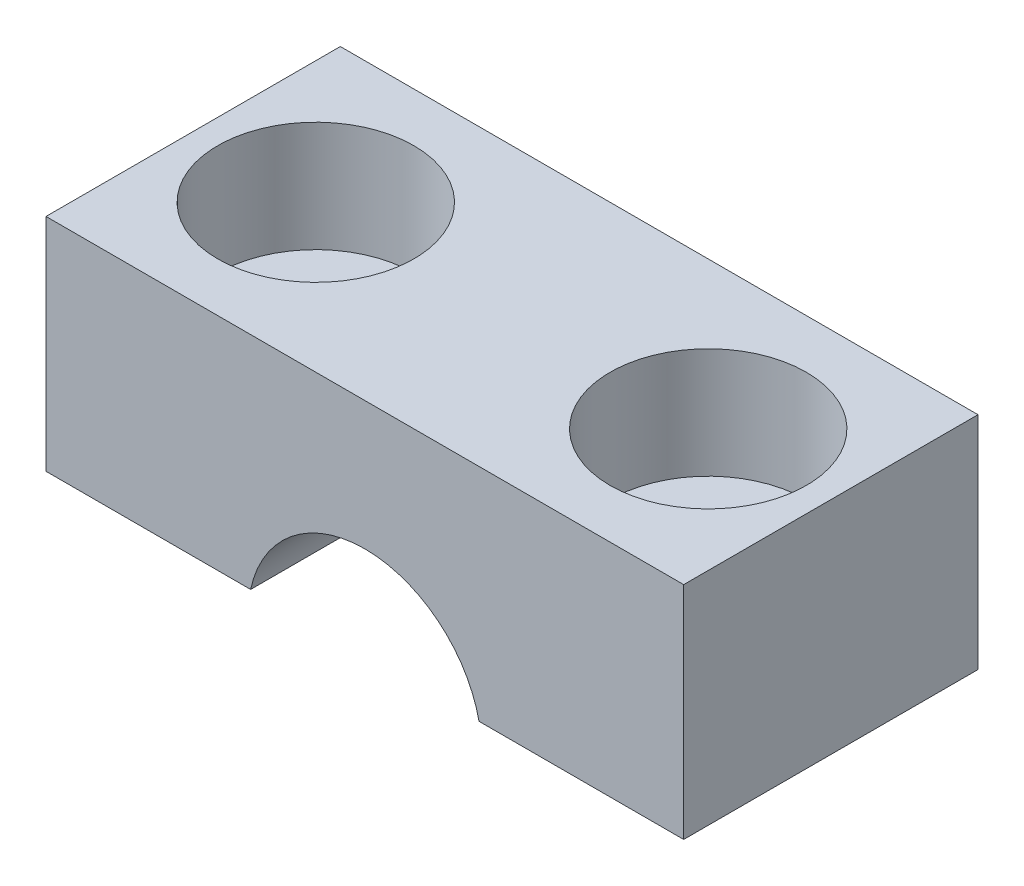
SolidWorks part; units mm, degrees
material "6061 Alloy"
ref_plane "Front Plane" through (0, 0, 0) normal (0, 0, 1) x (1, 0, 0)
ref_plane "Top Plane" through (0, 0, 0) normal (0, 1, 0) x (1, 0, 0)
ref_plane "Right Plane" through (0, 0, 0) normal (1, 0, 0) x (0, 0, -1)
ref_plane "Plane1" through (0, 35, 0) normal (0, 1, 0) x (1, 0, 0)
sketch "Sketch1" plane through (0, 35, 0) normal (0, 1, 0) x (1, 0, 0)
  line L0 (13, 6) -> (-13, 6)
  line L1 (-13, 6) -> (-13, -6)
  line L2 (-13, -6) -> (13, -6)
  line L3 (13, -6) -> (13, 6)
extrude "Boss-Extrude1" add sketch "Sketch1" against normal blind 9
sketch "Sketch2" plane through (0, 0, -6) normal (0, 0, -1) x (-1, 0, 0)
  line L0 (-4.6563, 26) -> (4.6563, 26)
  line L2 (-13, 26) -> (13, 26) construction
  arc A0 (4.6563, 26) -> (-4.6563, 26) centre (0, 25) ccw
  point P10 (0, 26)
  dimension "D1" = 4.7625
  dimension "D2" = 1
extrude "Cut-Extrude1" cut sketch "Sketch2" against normal through all
hole_wizard "CBORE for M4 Hex Head Machine Screw1" positions "Sketch4" profile "Sketch3" counterbore size "M4" standard "ANSI Metric"
sketch "Sketch4" plane through (0, 35, 0) normal (0, 1, 0) x (1, 0, 0)
  point P0 (-8, 0)
  point P1 (8, 0)
sketch "Sketch3" plane through (-8, 35, 0) normal (1, 0, 0) x (0, 0, 1)
  line L0 (0, 0) -> (0, 9)
  line L1 (0, 9) -> (2.25, 9)
  line L3 (2.25, 9) -> (2.25, 4.5)
  line L4 (2.25, 4.5) -> (4, 4.5)
  line L5 (4, 4.5) -> (4, 0)
  line L7 (4, 0) -> (0, 0)
  line L11 (0, -6.35) -> (0, 107.95) construction
  dimension "Thru Hole Dia." = 4.5
  dimension "Thru Hole Depth" = 9
  dimension "C'Bore Dia." = 8
  dimension "C'Bore Depth" = 4.5
